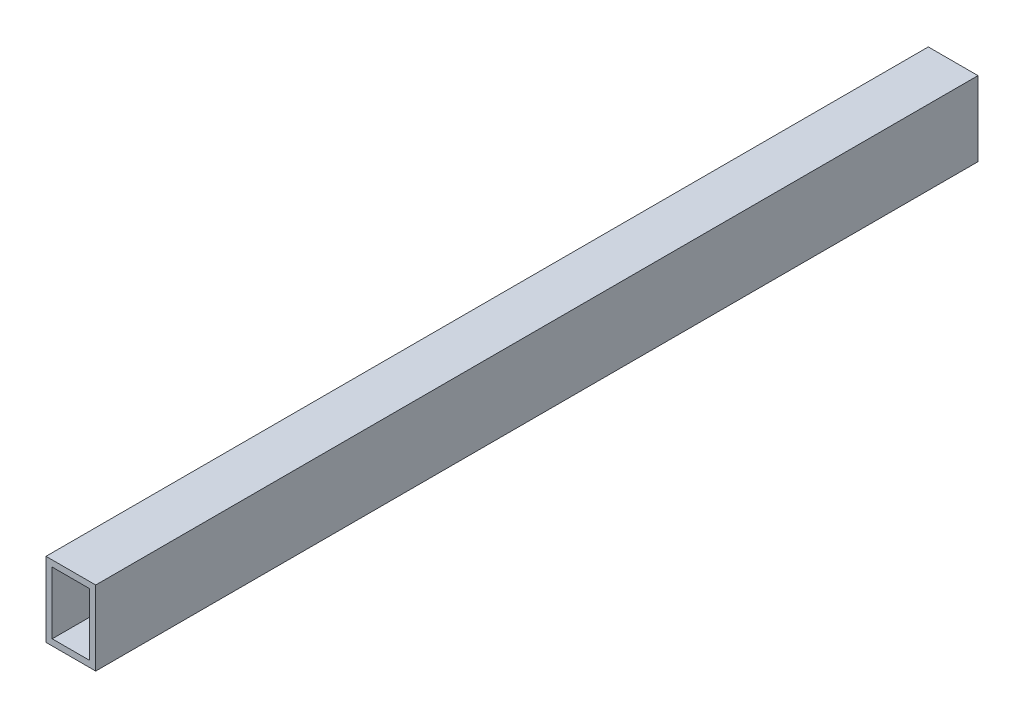
SolidWorks part; units mm, degrees
material "7075-T6 (SN)"
ref_plane "Front Plane" through (0, 0, 0) normal (0, 0, 1) x (1, 0, 0)
ref_plane "Top Plane" through (0, 0, 0) normal (0, 1, 0) x (1, 0, 0)
ref_plane "Right Plane" through (0, 0, 0) normal (1, 0, 0) x (0, 0, -1)
sketch "Sketch1" plane through (0, 0, 0) normal (0, 0, 1) x (1, 0, 0)
  line L1 (-25.4, -38.1) -> (25.4, -38.1)
  line L2 (-25.4, -38.1) -> (-25.4, 38.1)
  line L3 (-25.4, 38.1) -> (25.4, 38.1)
  line L4 (25.4, -38.1) -> (25.4, 38.1)
  line L5 (-25.4, -38.1) -> (25.4, 38.1) construction
  line L6 (-25.4, 38.1) -> (25.4, -38.1) construction
  line L7 (-19.05, -31.75) -> (19.05, -31.75)
  line L8 (-19.05, -31.75) -> (-19.05, 31.75)
  line L9 (-19.05, 31.75) -> (19.05, 31.75)
  line L10 (19.05, -31.75) -> (19.05, 31.75)
  line L11 (-19.05, -31.75) -> (19.05, 31.75) construction
  line L12 (-19.05, 31.75) -> (19.05, -31.75) construction
  point P0 (0, 0)
  point P6 (0, 0)
  dimension "D1" = 50.8
  dimension "D2" = 76.2
  dimension "D3" = 38.1
  dimension "D4" = 63.5
extrude "Boss-Extrude1" add sketch "Sketch1" along normal blind 901.7
equation "\"b_o\" = 2"
equation "\"h_o\" = 3"
equation "\"t\" = 0.25"
equation "\"w\" = 12.5"
equation "\"E\" = 10400000"
equation "\"rho\" = 0.1015"
equation "\"delta_max\" = 0.1"
equation "\"b_i\" = \"b_o\" - 2 * \"t\""
equation "\"h_i\" = \"h_o\" - 2 * \"t\""
equation "\"A\" = \"b_o\" * \"h_o\" - \"b_i\" * \"h_i\""
equation "\"I\" = ( \"b_o\" * \"h_o\" ^ 3 - \"b_i\" * \"h_i\" ^ 3 ) / 12"
equation "\"w_total\" = \"w\" + \"A\" * \"rho\""
equation "\"L_calc\" = ( 8 * \"E\" * \"I\" * \"delta_max\" / \"w_total\" ) ^ ( 1 / 4 )"
equation "\"L\" = int ( \"L_calc\" * 2 ) / 2"
equation "\"D1@Sketch1\" = \"b_o\""
equation "\"D2@Sketch1\" = \"h_o\""
equation "\"D3@Sketch1\" = \"b_i\""
equation "\"D4@Sketch1\" = \"h_i\""
equation "\"D1@Boss-Extrude1\" = \"L\""
